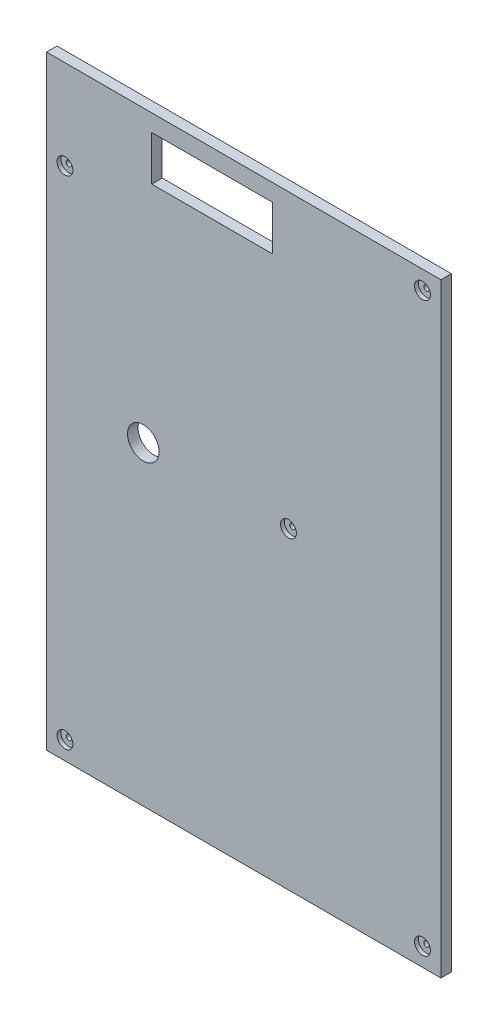
SolidWorks part; units mm, degrees
ref_plane "Front Plane" through (0, 0, 0) normal (0, 0, 1) x (1, 0, 0)
ref_plane "Top Plane" through (0, 0, 0) normal (0, 1, 0) x (1, 0, 0)
ref_plane "Right Plane" through (0, 0, 0) normal (1, 0, 0) x (0, 0, -1)
sketch "Sketch1" plane through (0, 0, 0) normal (0, 0, 1) x (1, 0, 0)
  line L1 (-75, -115) -> (75, -115)
  line L2 (-75, -115) -> (-75, 115)
  line L3 (-75, 115) -> (75, 115)
  line L4 (75, -115) -> (75, 115)
  line L5 (-75, -115) -> (75, 115) construction
  line L6 (-75, 115) -> (75, -115) construction
  point P1 (0, 0)
  dimension "D1" = 150
  dimension "D2" = 230
extrude "Boss-Extrude1" add sketch "Sketch1" along normal blind 4
sketch "Sketch3" plane through (0, 0, 0) normal (0, 0, -1) x (-1, 0, 0)
  line L4 (-64, 112) -> (-72, 104) construction
  line L8 (-72, 112) -> (-72, -112)
  line L9 (-72, -112) -> (72, -112)
  line L10 (72, -112) -> (72, 112)
  line L11 (72, 112) -> (-72, 112)
  line L12 (-72, 112) -> (-72, -112) construction
  line L13 (-72, -112) -> (72, -112) construction
  line L14 (72, -112) -> (72, 112) construction
  line L15 (72, 112) -> (-72, 112) construction
  line L17 (-72, 112) -> (-64, 112) construction
  line L18 (-72, 112) -> (-72, 104) construction
  line L19 (-72, 104) -> (-64, 104) construction
  line L20 (-64, 112) -> (-64, 104) construction
  line L21 (-72, -112) -> (-64, -112) construction
  line L22 (-72, -112) -> (-72, -104) construction
  line L23 (-72, -104) -> (-64, -104) construction
  line L24 (-64, -112) -> (-64, -104) construction
  line L25 (72, -112) -> (64, -112) construction
  line L26 (72, -112) -> (72, -104) construction
  line L27 (72, -104) -> (64, -104) construction
  line L28 (64, -112) -> (64, -104) construction
  line L29 (72, 85) -> (64, 85) construction
  line L30 (72, 85) -> (72, 77) construction
  line L31 (72, 77) -> (64, 77) construction
  line L32 (64, 85) -> (64, 77) construction
  line L33 (64, 81) -> (72, 81) construction
  line L34 (72, -104) -> (64, -112) construction
  line L35 (-64, -112) -> (-72, -104) construction
  point P19 (-68, 108)
  point P20 (68, 81)
  point P21 (68, -108)
  point P22 (-68, -108)
  point P23 (-17, 4)
  dimension "D2" = 8
  dimension "D3" = 27
  dimension "D4" = 55
  dimension "D5" = 116
  dimension "D1" = 3
hole_wizard "Tap Drill for M2.5x0.45 Tap2" positions "3DSketch2" profile "Sketch7" hole size "M2.5x0.45" standard "ANSI Metric" end condition up to next
sketch3d "3DSketch2"
  point P0 (68, 108, 0)
  point P3 (-68, 81, 0)
  point P6 (68, -108, 0)
  point P9 (-68, -108, 0)
  point P13 (17, 4, 0)
sketch "Sketch7" plane through (68, 108, 0) normal (1, 0, 0) x (0, 1, 0)
  line L0 (0, 0) -> (0, 4)
  line L1 (0, 4) -> (1.025, 4)
  line L2 (1.025, 4) -> (1.025, 0)
  line L5 (1.025, 0) -> (0, 0)
  line L11 (0, -6.35) -> (0, 107.95) construction
  dimension "Thru Hole Dia." = 2.05
  dimension "Thru Hole Depth" = 4
sketch "Sketch8" plane through (0, 0, 4) normal (0, 0, 1) x (1, 0, 0)
  circle A2 centre (-68, 81) radius 3.025
  circle A3 centre (-68, 81) radius 3.025
  circle A5 centre (68, 108) radius 3.025
  circle A6 centre (68, 108) radius 3.025
  circle A8 centre (-68, -108) radius 3.025
  circle A9 centre (-68, -108) radius 3.025
  circle A11 centre (68, -108) radius 3.025
  circle A12 centre (68, -108) radius 3.025
  circle A14 centre (17, 4) radius 3.025
  circle A15 centre (17, 4) radius 3.025
  dimension "D1" = 2
  dimension "D2" = 2
  dimension "D3" = 2
  dimension "D4" = 2
  dimension "D5" = 2
extrude "Cut-Extrude2" cut sketch "Sketch8" against normal blind 1.5
sketch "Sketch9" plane through (0, 0, 4) normal (0, 0, 1) x (1, 0, 0)
  line L0 (-75, 115) -> (75, 115) construction
  line L1 (-35, 108.5) -> (11, 108.5)
  line L2 (-35, 108.5) -> (-35, 91.5)
  line L3 (-35, 91.5) -> (11, 91.5)
  line L4 (11, 108.5) -> (11, 91.5)
  line L5 (-12, 91.5) -> (-12, 108.5) construction
  line L6 (-35, 100) -> (11, 100) construction
  line L7 (-75, -115) -> (-75, 115) construction
  point P160 (-12, 100)
  dimension "D1" = 6.5
  dimension "D2" = 17
  dimension "D3" = 40
  dimension "D4" = 46
extrude "Cut-Extrude3" cut sketch "Sketch9" against normal up to next and the other way through all
sketch "Sketch10" plane through (0, 0, 4) normal (0, 0, 1) x (1, 0, 0)
  circle A0 centre (-38.2023, 4.6924) radius 6
  dimension "D1" = 12
extrude "Cut-Extrude4" cut sketch "Sketch10" against normal up to next
